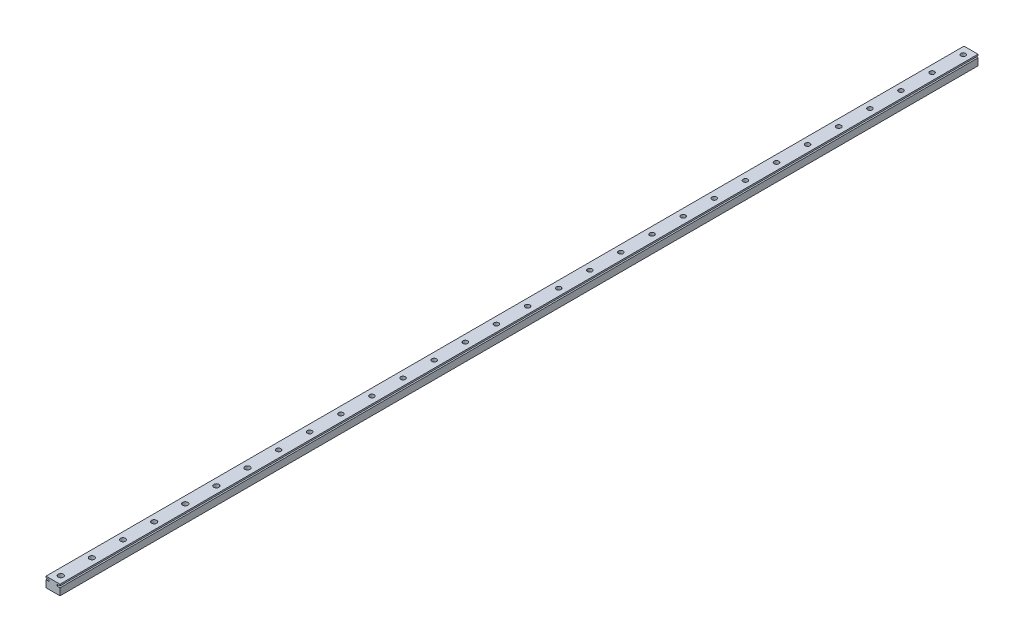
SolidWorks part; units mm, degrees
ref_plane "前视基准面" through (0, 0, 0) normal (0, 0, 1) x (1, 0, 0)
ref_plane "上视基准面" through (0, 0, 0) normal (0, 1, 0) x (1, 0, 0)
ref_plane "右视基准面" through (0, 0, 0) normal (1, 0, 0) x (0, 0, -1)
other "Configuration Table"
sketch "草图1" plane through (0, 0, 0) normal (0, 0, 1) x (1, 0, 0)
  line L1 (0, 0) -> (-9, 0)
  line L2 (0, 0) -> (0, 6.5)
  line L3 (0, 6.5) -> (-9, 6.5)
  line L4 (-9, 0) -> (-9, 6.5)
  dimension "D1" = 9
  dimension "D2" = 6.5
extrude "凸台-拉伸1" add sketch "草图1" along normal blind 590
sketch "草图2" plane through (0, 0, 0) normal (0, 0, -1) x (-1, 0, 0)
  line L0 (0, 6.5) -> (0, 5.5) construction
  line L1 (0, 0) -> (0, 6.5) construction
  line L2 (2, 5.5) -> (0, 5.5)
  line L3 (2, 4.5) -> (0, 4.5)
  line L4 (0, 4.5) -> (0, 5.5)
  line L5 (2, 5.5) -> (2, 4.5)
  line L6 (4.5, 6.5) -> (4.5, 5.0177) construction
  line L7 (0, 6.5) -> (9, 6.5) construction
  line L8 (7, 5.5) -> (9, 5.5)
  line L9 (9, 4.5) -> (9, 5.5)
  line L10 (7, 4.5) -> (9, 4.5)
  line L11 (7, 5.5) -> (7, 4.5)
  dimension "D1" = 1
  dimension "D2" = 1
  dimension "D3" = 2
extrude "切除-拉伸1" cut sketch "草图2" against normal blind 610
sketch "草图3" plane through (0, 6.5, 0) normal (0, 1, 0) x (1, 0, 0)
  line L0 (-4.5, 0) -> (-4.5, -5) construction
  line L1 (0, 0) -> (-9, 0) construction
  circle A0 centre (-4.5, -5) radius 1.5
  circle A1 centre (-4.5, -25) radius 1.5
  circle A2 centre (-4.5, -45) radius 1.5
  circle A3 centre (-4.5, -65) radius 1.5
  circle A4 centre (-4.5, -85) radius 1.5
  circle A5 centre (-4.5, -105) radius 1.5
  circle A6 centre (-4.5, -125) radius 1.5
  circle A7 centre (-4.5, -145) radius 1.5
  circle A8 centre (-4.5, -165) radius 1.5
  circle A9 centre (-4.5, -185) radius 1.5
  circle A10 centre (-4.5, -205) radius 1.5
  circle A11 centre (-4.5, -225) radius 1.5
  circle A12 centre (-4.5, -245) radius 1.5
  circle A13 centre (-4.5, -265) radius 1.5
  circle A14 centre (-4.5, -285) radius 1.5
  circle A15 centre (-4.5, -305) radius 1.5
  circle A16 centre (-4.5, -325) radius 1.5
  circle A17 centre (-4.5, -345) radius 1.5
  circle A18 centre (-4.5, -365) radius 1.5
  circle A19 centre (-4.5, -385) radius 1.5
  circle A20 centre (-4.5, -405) radius 1.5
  circle A21 centre (-4.5, -425) radius 1.5
  circle A22 centre (-4.5, -445) radius 1.5
  dimension "D2" = 3
  dimension "D1" = 5
  dimension "D3" = 23
extrude "切除-拉伸2" cut sketch "草图3" against normal up to next
sketch "草图4" plane through (0, 6.5, 0) normal (0, 1, 0) x (1, 0, 0)
  line L0 (-4.5, -445) -> (-4.5, -465) construction
  circle A0 centre (-4.5, -465) radius 1.6565
  circle A1 centre (-4.5, -485) radius 1.6565
  circle A2 centre (-4.5, -505) radius 1.6565
  circle A3 centre (-4.5, -525) radius 1.6565
  circle A4 centre (-4.5, -545) radius 1.6565
  circle A5 centre (-4.5, -565) radius 1.6565
  circle A6 centre (-4.5, -585) radius 1.6565
  dimension "D1" = 20
  dimension "D2" = 7
extrude "切除-拉伸3" cut sketch "草图4" against normal blind 10
